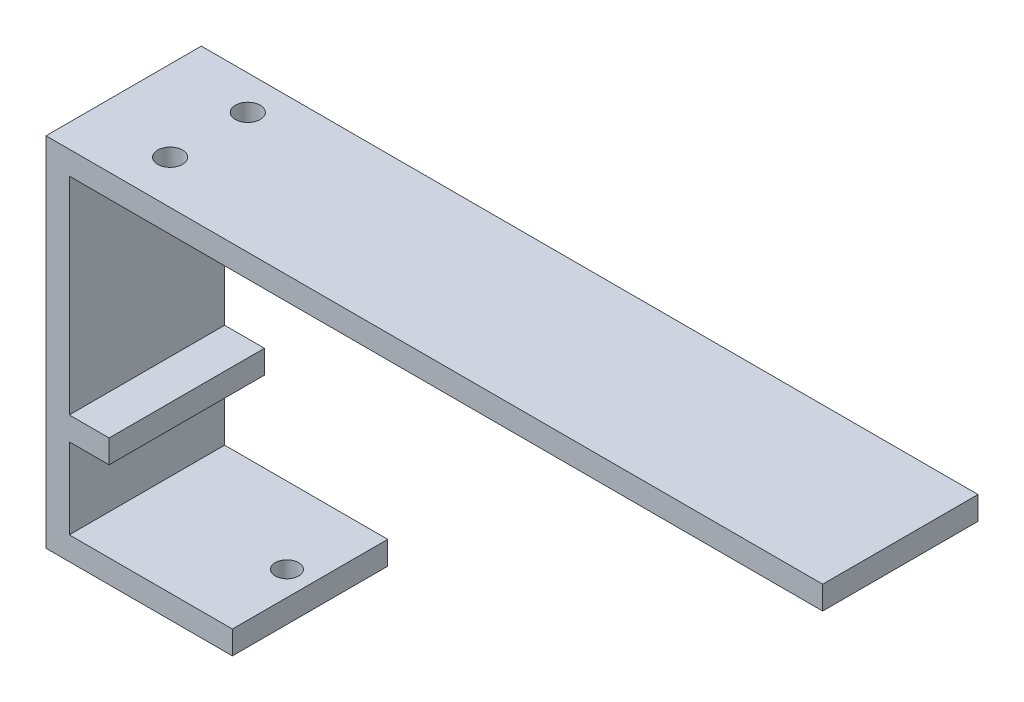
SolidWorks part; units mm, degrees
ref_plane "Front" through (0, 0, 0) normal (0, 0, 1) x (1, 0, 0)
ref_plane "Top" through (0, 0, 0) normal (0, 1, 0) x (1, 0, 0)
ref_plane "Right" through (0, 0, 0) normal (1, 0, 0) x (0, 0, -1)
sketch "Sketch1" plane through (0, 0, 0) normal (0, 1, 0) x (1, 0, 0)
  line L1 (0, 0) -> (100, 0)
  line L2 (0, 0) -> (0, 20)
  line L3 (0, 20) -> (100, 20)
  line L4 (100, 0) -> (100, 20)
  dimension "D1" = 100
  dimension "D2" = 20
extrude "Boss-Extrude1" add sketch "Sketch1" along normal blind 3
sketch "Sketch4" plane through (0, 0, -20) normal (0, 0, -1) x (-1, 0, 0)
  line L1 (0, 0) -> (-3, 0)
  line L2 (0, 0) -> (0, -43)
  line L3 (0, -43) -> (-3, -43)
  line L4 (-3, 0) -> (-3, -43)
  line L6 (-3, -24) -> (-3, -26.6921)
  dimension "D1" = 43
  dimension "D4" = 3
extrude "Boss-Extrude3" add sketch "Sketch4" against normal blind 20
sketch "Sketch8" plane through (0, 0, -20) normal (0, 0, -1) x (-1, 0, 0)
  line L0 (0, 3) -> (0, -43) construction
  line L1 (-24, -40) -> (0, -40)
  line L2 (-24, -40) -> (-24, -43)
  line L3 (-24, -43) -> (0, -43)
  line L4 (0, -40) -> (0, -43)
  line L5 (0, -43) -> (-3, -43) construction
  dimension "D1" = 24
  dimension "D2" = 0
  dimension "D3" = 0
  dimension "D4" = 3
extrude "Boss-Extrude6" add sketch "Sketch8" against normal blind 20
sketch "Sketch10" plane through (0, 0, 0) normal (0, 0, 1) x (1, 0, 0)
  line L0 (3, -40) -> (24, -40) construction
  line L1 (2.1265, -29.63) -> (8.1265, -29.63)
  line L2 (2.1265, -29.63) -> (2.1265, -26.63)
  line L3 (2.1265, -26.63) -> (8.1265, -26.63)
  line L4 (8.1265, -29.63) -> (8.1265, -26.63)
  dimension "D1" = 10.37
  dimension "D2" = 3
  dimension "D3" = 6
extrude "Boss-Extrude9" add sketch "Sketch10" against normal blind 20
sketch "Sketch11" plane through (0, -43, 0) normal (0, -1, 0) x (1, 0, 0)
  circle A0 centre (20.8527, -10.1658) radius 1.5
sketch "Sketch12" plane through (0, -43, 0) normal (0, -1, 0) x (-1, 0, 0)
  line L0 (0, 0) -> (0, 20) construction
  line L1 (0, 0) -> (-24, 0) construction
  circle A0 centre (-10.38, 5.6) radius 1.6
  circle A1 centre (-10.38, 15.6) radius 1.6
  dimension "D2" = 5.6
  dimension "D3" = 10
  dimension "D1" = 10.38
extrude "Cut-Extrude1" cut sketch "Sketch12" against normal blind 80
extrude "Cut-Extrude2" cut sketch "Sketch11" against normal blind 20 contours A0
sketch "Sketch13" plane through (0, -43, 0) normal (0, -1, 0) x (1, 0, 0)
  line L1 (5.0707, -18.7755) -> (13.032, -18.7755)
  line L2 (5.0707, -18.7755) -> (5.0707, -3.4745)
  line L3 (5.0707, -3.4745) -> (13.032, -3.4745)
  line L4 (13.032, -18.7755) -> (13.032, -3.4745)
extrude "Boss-Extrude10" add sketch "Sketch13" against normal blind 3
sketch "Sketch14" plane through (0, 0, 0) normal (0, -1, 0) x (-1, 0, 0)
  line L0 (-3, 0) -> (-100, 0) construction
  line L1 (-63.4991, 0) -> (-56.0346, 0)
  line L2 (-63.4991, 0) -> (-63.4991, 20)
  line L3 (-63.4991, 20) -> (-56.0346, 20)
  line L4 (-56.0346, 0) -> (-56.0346, 20)
  line L5 (-100, 20) -> (-3, 20) construction
sketch "Sketch18" plane through (0, -43, 0) normal (0, -1, 0) x (1, 0, 0)
  line L0 (24, 0) -> (32.8053, 9.7793)
  line L1 (32.8053, 9.7793) -> (48.8053, 9.7793)
  line L2 (48.8053, 9.7793) -> (48.8053, 12.3849)
  line L3 (48.8053, 12.3849) -> (31.1145, 12.3849)
  line L4 (31.1145, 12.3849) -> (19.9631, 0)
  line L5 (0, 0) -> (24, 0) construction
  line L6 (19.9631, 0) -> (24, 0)
  dimension "D1" = 132
  dimension "D2" = 3
  dimension "D3" = 16
